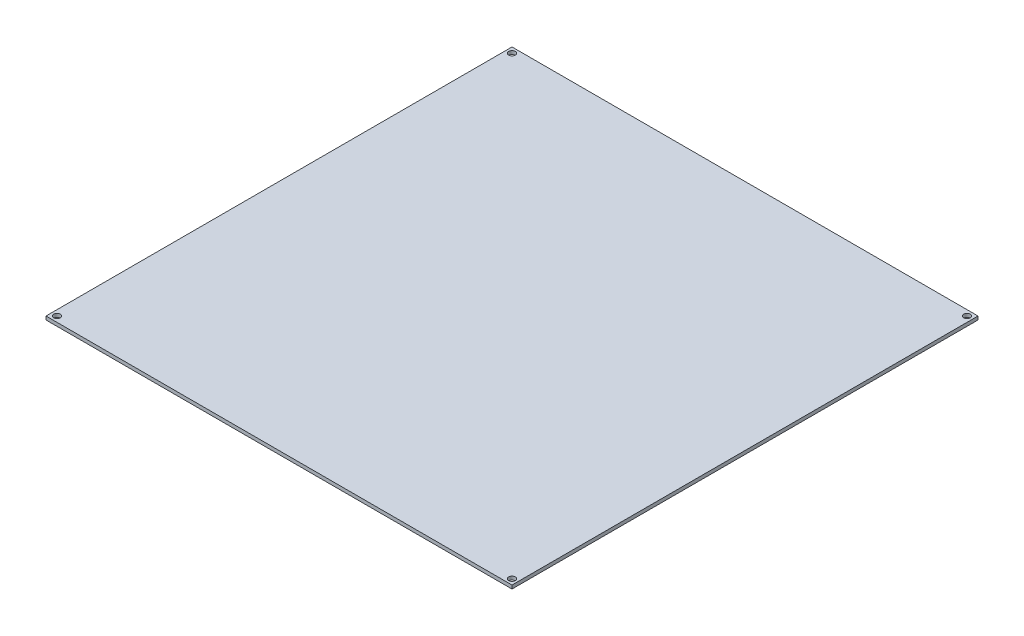
SolidWorks part; units mm, degrees
ref_plane "Front Plane" through (0, 0, 0) normal (0, 0, 1) x (1, 0, 0)
ref_plane "Top Plane" through (0, 0, 0) normal (0, 1, 0) x (1, 0, 0)
ref_plane "Right Plane" through (0, 0, 0) normal (1, 0, 0) x (0, 0, -1)
sketch "Sketch1" plane through (0, 0, 0) normal (0, 1, 0) x (1, 0, 0)
  line L0 (-107, -107) -> (107, 107) construction
  line L1 (-107, 107) -> (107, 107)
  line L2 (-107, 107) -> (-107, -107)
  line L3 (-107, -107) -> (107, -107)
  line L4 (107, 107) -> (107, -107)
  line L5 (0, 107) -> (0, -107) construction
  line L6 (107, 0) -> (-107, 0) construction
  circle A0 centre (-104.5, 104.5) radius 1.5
  circle A1 centre (104.5, 104.5) radius 1.5
  circle A2 centre (-104.5, -104.5) radius 1.5
  circle A3 centre (104.5, -104.5) radius 1.5
  dimension "D2" = 2.5
  dimension "D3" = 2.5
  dimension "D4" = 3
  dimension "D5" = 209
  dimension "D1" = 214
extrude "Boss-Extrude1" add sketch "Sketch1" along normal mid plane 1.6
